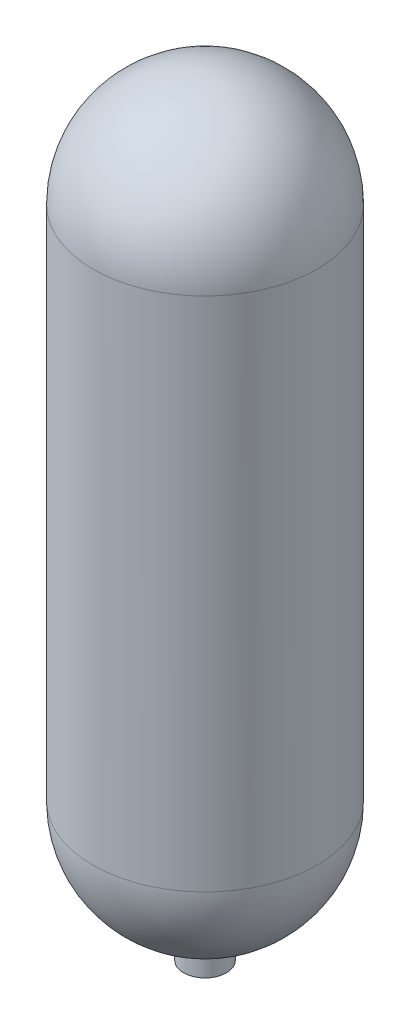
SolidWorks part; units mm, degrees
ref_plane "Front Plane" through (0, 0, 0) normal (0, 0, 1) x (1, 0, 0)
ref_plane "Top Plane" through (0, 0, 0) normal (0, 1, 0) x (1, 0, 0)
ref_plane "Right Plane" through (0, 0, 0) normal (1, 0, 0) x (0, 0, -1)
sketch "Sketch1" plane through (0, 0, 0) normal (0, 0, 1) x (1, 0, 0)
  line L0 (0, 0) -> (0, 747.3154) construction
  line L1 (0, 0) -> (15, 0)
  line L2 (15, 0) -> (15, 20)
  line L3 (78.5, 458.5) -> (78.5, 97.0536)
  line L4 (0, 537) -> (0, 0)
  arc A0 (78.5, 458.5) -> (0, 537) centre (0, 458.5) ccw
  arc A2 (15, 20) -> (78.5, 97.0536) centre (0, 97.0536) ccw
  dimension "D1" = 157
  dimension "D2" = 30
  dimension "D3" = 20
  dimension "D4" = 537
revolve "Revolve1" add sketch "Sketch1" angle 360 about L0
hole_wizard "M18x1.5 Tapped Hole1" positions "Sketch2" profile "Sketch3" tap size "M18x1.5" standard "ANSI Metric"
sketch "Sketch2" plane through (0, 0, 0) normal (0, -1, 0) x (-1, 0, 0)
  point P0 (0, 0)
sketch "Sketch3" plane through (0, 0, 0) normal (1, 0, 0) x (0, 0, -1)
  line L0 (0, 0) -> (0, 20)
  line L1 (0, 20) -> (8.25, 15.0429)
  line L2 (8.25, 15.0429) -> (8.25, 0)
  line L5 (8.25, 0) -> (0, 0)
  line L10 (0, 20) -> (-8.25, 15.0429) construction
  line L11 (0, -6.35) -> (0, 107.95) construction
  dimension "Tap Drill Dia." = 16.5
  dimension "Tap Drill Depth" = 20
  dimension "Drill Angle" = 118
cosmetic thread "Hole Thread1" parameters "D1"=36, "D2"=18
fillet "Fillet1" radius 5 1 edges at (0, 20, -15)
sketch "Sketch4" plane through (0, 0, 0) normal (0, 0, 1) x (1, 0, 0)
  line L0 (0, 0) -> (0, 652.9616) construction
  line L3 (8.25, 15.0429) -> (8.25, 25.6931)
  line L4 (73.5, 97.0536) -> (73.5, 458.5)
  line L5 (73.5, 97.0536) -> (73.5, 458.5)
  line L6 (8.25, 25.6931) -> (17.6048, 25.6931)
  line L7 (8.25, 15.0429) -> (0, 15.0429)
  line L8 (8.25, 15.0429) -> (-8.25, 15.0429) construction
  line L9 (0, 15.0429) -> (0, 532)
  arc A6 (73.5, 458.5) -> (-73.5, 458.5) centre (0, 458.5) ccw
  arc A7 (17.6048, 25.6931) -> (73.5, 97.0536) centre (0, 97.0536) ccw
  arc A8 (73.5, 458.5) -> (0, 532) centre (0, 458.5) ccw
  arc A9 (17.6048, 25.6931) -> (73.5, 97.0536) centre (0, 97.0536) ccw
  dimension "D1" = 5
revolve "Cut-Revolve1" cut sketch "Sketch4" angle 360 about L0
